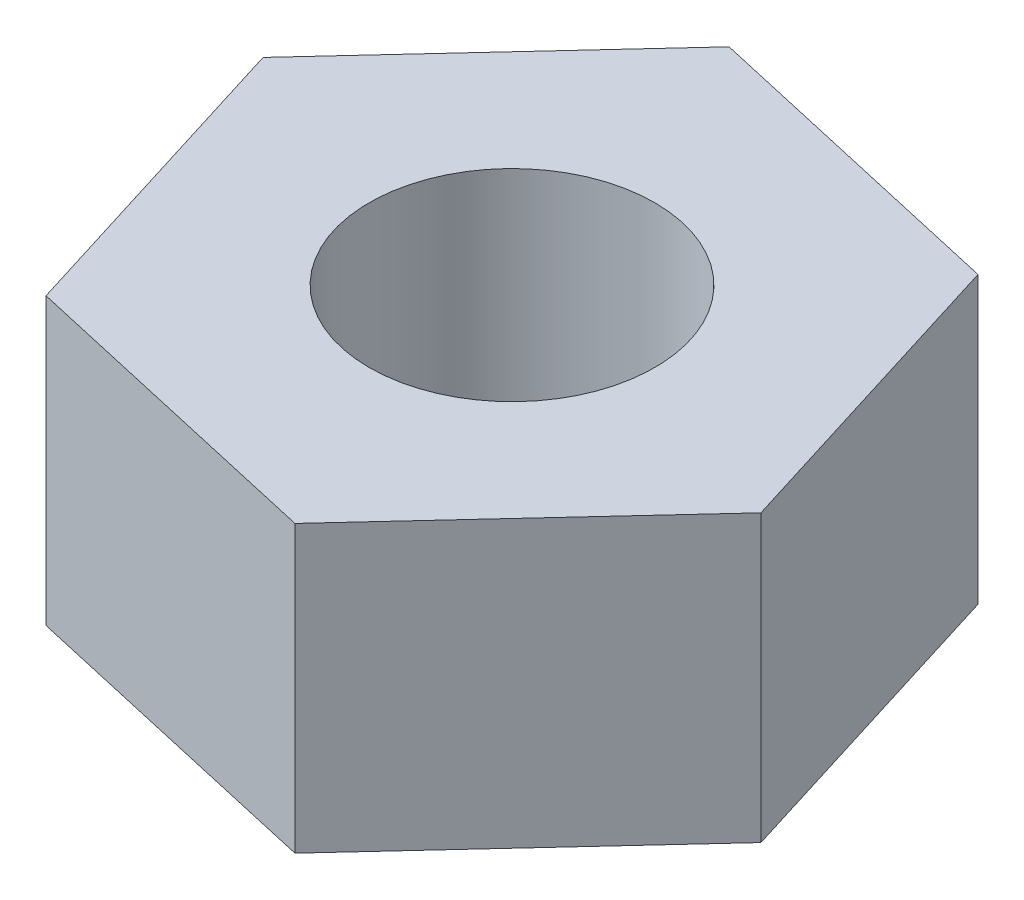
SolidWorks part; units mm, degrees
ref_plane "Plan de face" through (0, 0, 0) normal (0, 0, 1) x (1, 0, 0)
ref_plane "Plan de dessus" through (0, 0, 0) normal (0, 1, 0) x (1, 0, 0)
ref_plane "Plan de droite" through (0, 0, 0) normal (1, 0, 0) x (0, 0, -1)
ref_plane "Plan1" through (0, -3, 0) normal (0, -1, 0) x (1, 0, 0)
sketch "Esquisse1" plane through (0, -3, 0) normal (0, -1, 0) x (1, 0, 0)
  line L0 (2.3509, -2.5442) -> (3.3788, 0.7638)
  line L1 (3.3788, 0.7638) -> (1.0279, 3.3081)
  line L2 (1.0279, 3.3081) -> (-2.3509, 2.5442)
  line L3 (-2.3509, 2.5442) -> (-3.3788, -0.7638)
  line L4 (-3.3788, -0.7638) -> (-1.0279, -3.3081)
  line L5 (-1.0279, -3.3081) -> (2.3509, -2.5442)
  circle A0 centre (0, 0) radius 1.5
extrude "Boss.-Extru.1" add sketch "Esquisse1" against normal blind 3
